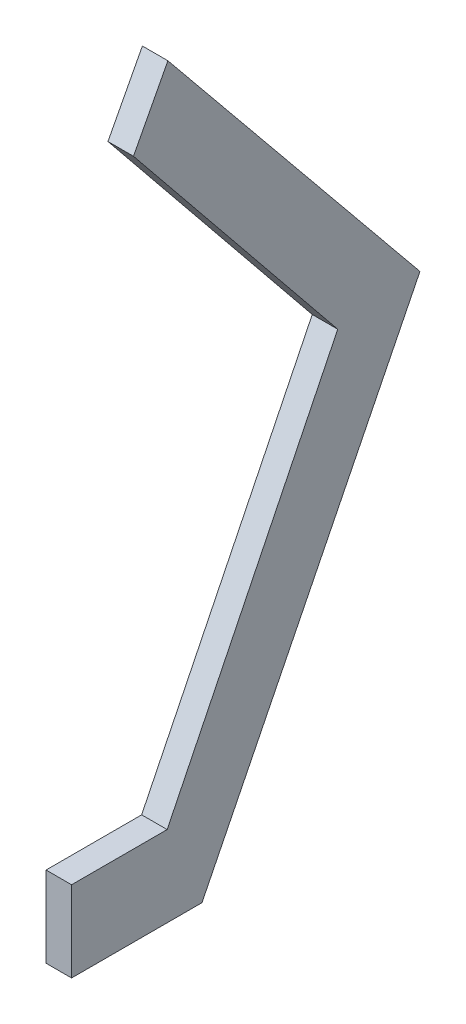
SolidWorks part; units mm, degrees
ref_plane "Front Plane" through (0, 0, 0) normal (0, 0, 1) x (1, 0, 0)
ref_plane "Top Plane" through (0, 0, 0) normal (0, 1, 0) x (1, 0, 0)
ref_plane "Right Plane" through (0, 0, 0) normal (1, 0, 0) x (0, 0, -1)
sketch "Sketch1" plane through (0, 0, 0) normal (1, 0, 0) x (0, 0, -1)
  line L0 (0, 0) -> (-12.7742, 0)
  line L5 (-12.7742, 0) -> (-12.7742, 7.9118)
  line L6 (-12.7742, 7.9118) -> (-3.4098, 7.9118)
  line L7 (-3.4098, 7.9118) -> (13.304, 42.0052)
  line L8 (13.304, 42.0052) -> (-6.7094, 66.6891)
  line L9 (-6.7094, 66.6891) -> (-3.3367, 73.1064)
  line L10 (-3.3367, 73.1064) -> (21.3564, 42.8843)
  line L11 (21.3564, 42.8843) -> (0, 0)
  point P5 (-6.7094, 66.6891)
extrude "Boss-Extrude1" add sketch "Sketch1" along normal mid plane 2.5
